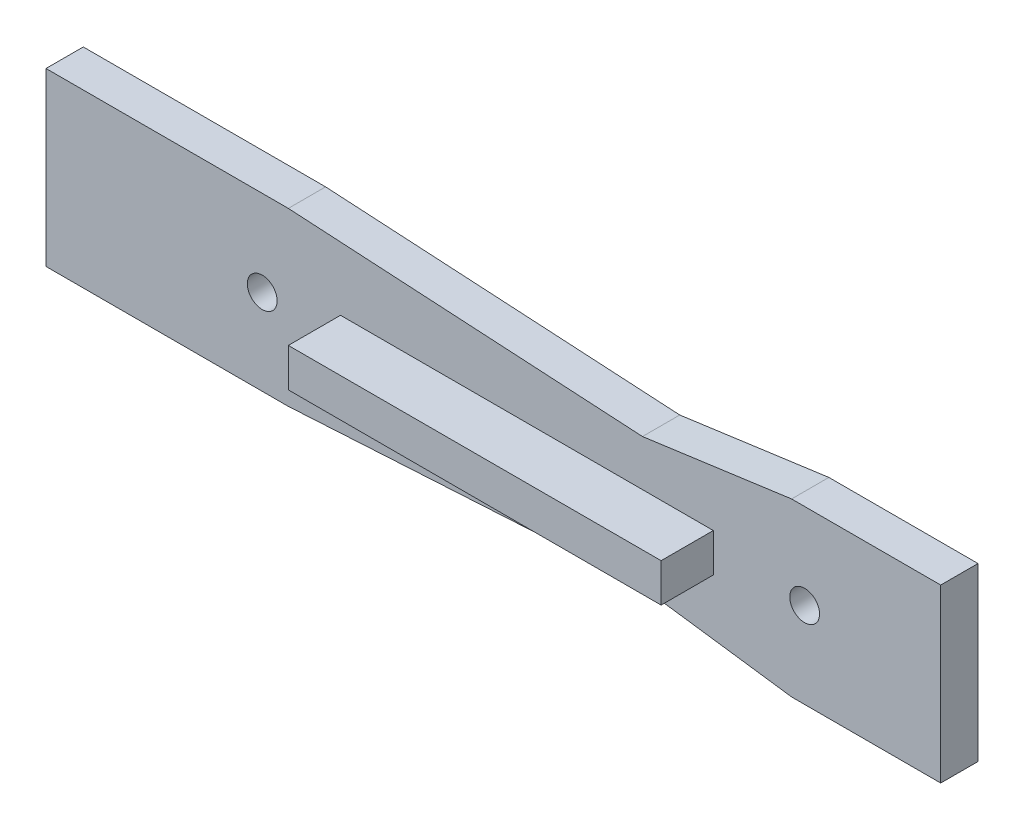
SolidWorks part; units mm, degrees
ref_plane "前视基准面" through (0, 0, 0) normal (0, 0, 1) x (1, 0, 0)
ref_plane "上视基准面" through (0, 0, 0) normal (0, 1, 0) x (1, 0, 0)
ref_plane "右视基准面" through (0, 0, 0) normal (1, 0, 0) x (0, 0, -1)
other "Configuration Table"
sketch "草图1" plane through (0, 0, 0) normal (0, 0, 1) x (1, 0, 0)
  line L0 (0, 0) -> (50000, 0) construction
  line L1 (0, 0) -> (0, 50000) construction
  line L3 (-120, 23) -> (120, 23)
  line L4 (-120, 23) -> (-120, -23)
  line L5 (-120, -23) -> (120, -23)
  line L6 (120, 23) -> (120, -23)
extrude "凸台-拉伸1" add sketch "草图1" along normal blind 10
sketch "草图2" plane through (0, 0, 10) normal (0, 0, 1) x (1, 0, 0)
  line L0 (0, 0) -> (0, 50000) construction
  line L1 (0, 0) -> (50000, 0) construction
  line L2 (-120, 23) -> (-120, -23) construction
  line L3 (-55, 21) -> (40, 21)
  line L4 (-55, 21) -> (-55, -21)
  line L5 (-55, -21) -> (40, -21)
  line L6 (40, 21) -> (40, -21)
  line L7 (-120, -23) -> (120, -23) construction
  line L8 (-55, 17.5) -> (40, 17.5)
  line L9 (-55, 17.5) -> (-55, -17.5)
  line L10 (-55, -17.5) -> (40, -17.5)
  line L11 (40, 17.5) -> (40, -17.5)
  line L12 (120, 23) -> (80, 23)
  line L13 (120, 23) -> (120, -23)
  line L14 (120, -23) -> (80, -23)
  line L15 (80, 23) -> (80, -23)
  line L16 (40, 17.5) -> (80, 23)
  line L17 (80, -23) -> (40, -17.5)
  line L18 (-55, 21) -> (-55, 23)
  line L19 (120, 23) -> (-120, 23) construction
  line L20 (-55, 23) -> (-55, -23)
  line L21 (-55, 23) -> (40, 17.5)
  line L22 (40, -17.5) -> (-55, -23)
  line M12 (-120, -23) -> (120, -23)
  line M14 (120, 23) -> (-120, 23)
  dimension "D1" = 65
  dimension "D2" = 35
extrude "切除-拉伸1" cut sketch "草图2" against normal blind 10 contours L21 L3 L6 L16 M14 | L5 L22 L17 L6 M12 | L6 L22 L5 | L3 L21 L6
sketch "草图3" plane through (0, 0, 10) normal (0, 0, 1) x (1, 0, 0)
  line L0 (0, 0) -> (50000, 0) construction
  line L1 (0, 0) -> (0, 50000) construction
  line L2 (-120, 23) -> (-120, -23) construction
  line L3 (-45, 5) -> (21.7468, 5)
  line L4 (-45, 5) -> (-45, -5)
  line L5 (-45, -5) -> (21.7468, -5)
  line L6 (21.7468, 5) -> (21.7468, -5)
  dimension "D1" = 75
extrude "凸台-拉伸3" add sketch "草图3" along normal blind 14
sketch "草图5" plane through (0, 0, 10) normal (0, 0, 1) x (1, 0, 0)
  line L0 (0, 0) -> (50000, 0) construction
  line L1 (0, 0) -> (0, 50000) construction
  line L2 (120, -23) -> (120, 23) construction
  circle A0 centre (83.5, 0) radius 12.5
  dimension "D1" = 36.5
extrude "切除-拉伸2" cut sketch "草图5" against normal blind 14 contours A0
sketch "草图6" plane through (0, 0, 10) normal (0, 0, 1) x (1, 0, 0)
  line L0 (0, 0) -> (50000, 0) construction
  line L1 (0, 0) -> (0, 50000) construction
  line L2 (-120, 23) -> (-120, -23) construction
  circle A0 centre (-62, 0) radius 4
  dimension "D1" = 58
extrude "切除-拉伸3" cut sketch "草图6" against normal blind 10 contours A0
sketch "草图7" plane through (0, -5, 0) normal (0, -1, 0) x (1, 0, 0)
  line L1 (-45, 24) -> (21.7468, 24)
  line L2 (-45, 24) -> (-45, 10)
  line L3 (-45, 10) -> (21.7468, 10)
  line L4 (21.7468, 24) -> (21.7468, 10)
extrude "切除-拉伸4" cut sketch "草图7" against normal blind 10
sketch "草图8" plane through (0, 0, 10) normal (0, 0, 1) x (1, 0, 0)
  line L0 (0, 0) -> (50000, 0) construction
  line L1 (0, 0) -> (0, 50000) construction
  line L2 (120, -23) -> (120, 23) construction
  line L3 (-41, 5.164) -> (59, 5.164)
  line L4 (-41, 5.164) -> (-41, -5.164)
  line L5 (-41, -5.164) -> (59, -5.164)
  line L6 (59, 5.164) -> (59, -5.164)
  dimension "D1" = 61
extrude "凸台-拉伸4" add sketch "草图8" along normal blind 14 contours L4 L3 L6 L5
sketch "草图9" plane through (0, 0, 10) normal (0, 0, 1) x (1, 0, 0)
  line L0 (0, 0) -> (50000, 0) construction
  line L1 (0, 0) -> (0, 50000) construction
  circle A0 centre (83.5, 0) radius 4
  circle A1 centre (83.5, 0) radius 12.5
extrude "凸台-拉伸5" add sketch "草图9" against normal blind 10
